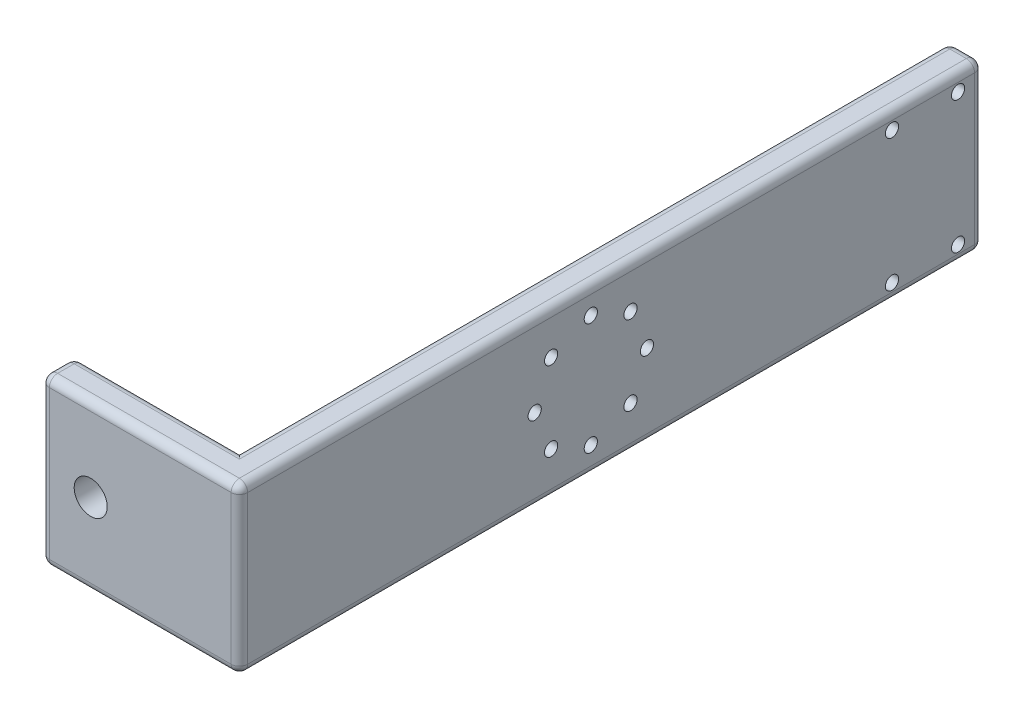
SolidWorks part; units mm, degrees
ref_plane "Front Plane" through (0, 0, 0) normal (0, 0, 1) x (1, 0, 0)
ref_plane "Top Plane" through (0, 0, 0) normal (0, 1, 0) x (1, 0, 0)
ref_plane "Right Plane" through (0, 0, 0) normal (1, 0, 0) x (0, 0, -1)
sketch "Sketch1" plane through (0, 0, 0) normal (0, 1, 0) x (1, 0, 0)
  line L0 (50, 20) -> (50, 450)
  line L2 (-50, 0) -> (-50, 20)
  line L3 (-50, 20) -> (50, 20)
  line L5 (-50, 0) -> (70, 0)
  line L8 (70, 0) -> (70, 450)
  line L9 (70, 450) -> (50, 450)
  dimension "D5" = 450
  dimension "D2" = 100
  dimension "D3" = 50
  dimension "D1" = 20
extrude "Boss-Extrude1" add sketch "Sketch1" along normal blind 100
sketch "Sketch4" plane through (0, 0, 0) normal (0, 0, 1) x (1, 0, 0)
  line L0 (-50, 100) -> (-50, 0) construction
  line L2 (-50, 0) -> (70, 0) construction
  circle A0 centre (-20, 50) radius 10
  dimension "D1" = 20
  dimension "D2" = 30
  dimension "D3" = 50
extrude "Cut-Extrude2" cut sketch "Sketch4" against normal through all and the other way through all
fillet "Fillet1" radius 5 17 edges at (60, 100, -450) (50, 50, -450) (60, 0, -450) (50, 0, -235) (0, 0, -20) (-50, 0, -10) (-50, 50, -20) (-50, 100, -10) (0, 100, -20) (50, 100, -235) (10, 0, 0) (-50, 50, 0) (10, 100, 0) (70, 100, -225) (70, 0, -225) (70, 50, -450) (70, 50, 0)
sketch "Sketch5" plane through (70, 0, 0) normal (1, 0, 0) x (0, 0, -1)
  line L0 (5, 50) -> (445, 50) construction
  line L1 (5, 95) -> (5, 5) construction
  line L2 (445, 5) -> (445, 95) construction
  line L3 (212.7, 83.9706) -> (212.7, 50) construction
  circle A14 centre (212.7, 50) radius 33.9706
  circle A15 centre (212.7, 83.9706) radius 4
  circle A16 centre (236.7208, 74.0208) radius 4
  circle A17 centre (246.6706, 50) radius 4
  circle A18 centre (236.7208, 25.9792) radius 4
  circle A19 centre (212.7, 16.0294) radius 4
  circle A20 centre (188.6792, 25.9792) radius 4
  circle A21 centre (178.7294, 50) radius 4
  circle A22 centre (188.6792, 74.0208) radius 4
  point P6 (212.7, 50)
  point P26 (212.7, 50)
  point P42 (212.7, 50)
  dimension "D3" = 8
  dimension "D2" = 67.9412
  dimension "D1" = 207.7
  dimension "D5" = 8
extrude "Cut-Extrude3" cut sketch "Sketch5" against normal blind 15 contours A15 | A16 | A17 | A19 | A18 | A22 | A21 | A20
cosmetic thread "Cosmetic Thread1" parameters "D2"=10
cosmetic thread "Cosmetic Thread2" parameters "D2"=10
cosmetic thread "Cosmetic Thread3" parameters "D2"=10
cosmetic thread "Cosmetic Thread4" parameters "D2"=10
cosmetic thread "Cosmetic Thread5" parameters "D2"=10
cosmetic thread "Cosmetic Thread6" parameters "D2"=10
cosmetic thread "Cosmetic Thread7" parameters "D2"=10
cosmetic thread "Cosmetic Thread21" parameters "D2"=10
sketch "Sketch6" plane through (70, 0, 0) normal (1, 0, 0) x (0, 0, -1)
  circle A4 centre (395, 10) radius 4
  circle A5 centre (435, 10) radius 4
  circle A6 centre (435, 90) radius 4
  circle A7 centre (395, 90) radius 4
extrude "Cut-Extrude4" cut sketch "Sketch6" against normal blind 20
cosmetic thread "Cosmetic Thread9" parameters "D2"=10
cosmetic thread "Cosmetic Thread10" parameters "D2"=10
cosmetic thread "Cosmetic Thread11" parameters "D2"=10
cosmetic thread "Cosmetic Thread12" parameters "D2"=10
sketch "Sketch7" plane through (50, 0, 0) normal (-1, 0, 0) x (0, 0, 1)
  circle A0 centre (-363.0438, 72.225) radius 3
  circle A1 centre (-328.1188, 72.225) radius 3
  circle A2 centre (-363.0438, 27.775) radius 3
  circle A3 centre (-328.1188, 27.775) radius 3
  dimension "D1" = 6
  dimension "D2" = 6
  dimension "D3" = 6
  dimension "D4" = 6
extrude "Cut-Extrude5" cut sketch "Sketch7" against normal blind 13
cosmetic thread "Cosmetic Thread13" parameters "D1"=5, "D2"=10
cosmetic thread "Cosmetic Thread14" parameters "D1"=5, "D2"=10
cosmetic thread "Cosmetic Thread15" parameters "D1"=5, "D2"=10
cosmetic thread "Cosmetic Thread16" parameters "D1"=5, "D2"=10
cosmetic thread "Cosmetic Thread17" parameters "D2"=10
cosmetic thread "Cosmetic Thread18" parameters "D2"=10
cosmetic thread "Cosmetic Thread19" parameters "D2"=10
cosmetic thread "Cosmetic Thread20" parameters "D2"=10
equation "\"COREF\" = 0.2077m"
equation "\"D1@Sketch5\" = \"COREF\""
equation "\"hipMember2_T\" = 0.0200m"
equation "\"D1@Sketch1\" = \"hipMember2_T\""
